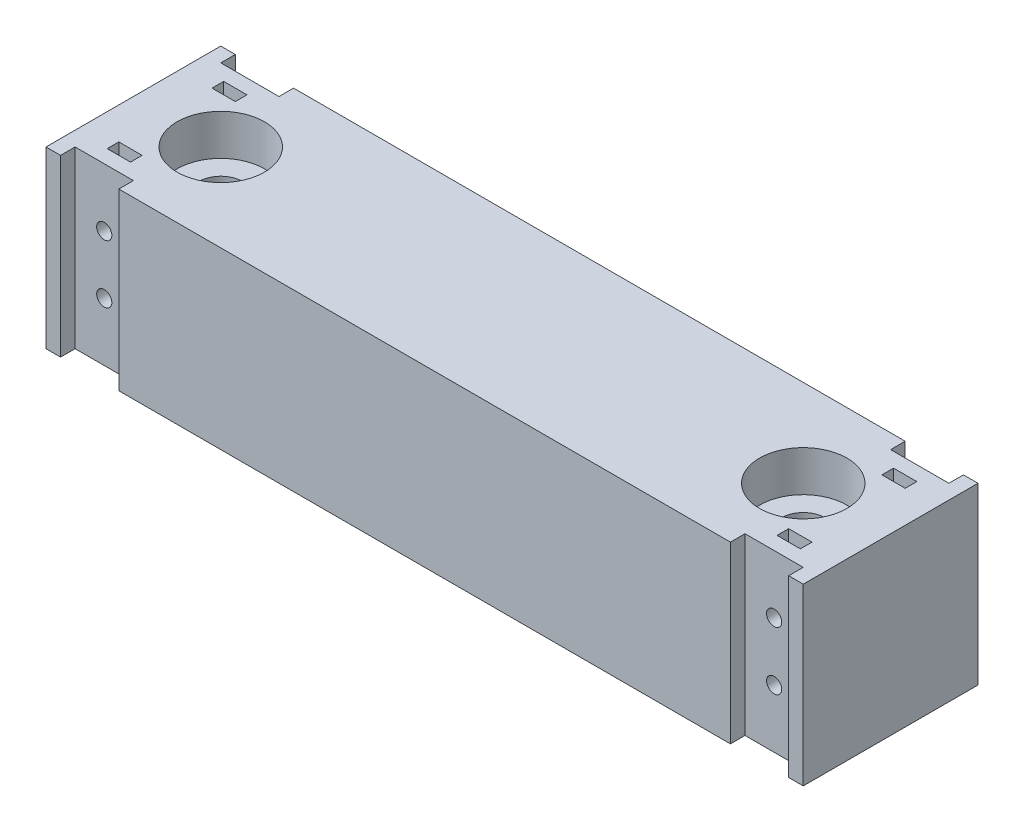
SolidWorks part; units mm, degrees
ref_plane "Płaszczyzna przednia" through (0, 0, 0) normal (0, 0, 1) x (1, 0, 0)
ref_plane "Płaszczyzna górna" through (0, 0, 0) normal (0, 1, 0) x (1, 0, 0)
ref_plane "Płaszczyzna prawa" through (0, 0, 0) normal (1, 0, 0) x (0, 0, -1)
sketch "Sketch1" plane through (0, 0, 0) normal (1, 0, 0) x (0, 0, -1)
  line L1 (0, 0) -> (60, 0)
  line L2 (0, 0) -> (0, 60)
  line L3 (0, 60) -> (60, 60)
  line L4 (60, 0) -> (60, 60)
  dimension "D1" = 60
  dimension "D2" = 60
extrude "Boss-Extrude1" add sketch "Sketch1" along normal blind 260
sketch "Sketch2" plane through (0, 0, 0) normal (0, 1, 0) x (1, 0, 0)
  line L0 (0, 60) -> (0, 0) construction
  line L1 (260, 0) -> (0, 0) construction
  line L2 (260, 60) -> (260, 0) construction
  circle A0 centre (30, 30) radius 7.5
  circle A1 centre (230, 30) radius 7.5
  dimension "D1" = 15
  dimension "D3" = 30
  dimension "D4" = 30
  dimension "D2" = 30
extrude "Cut-Extrude1" cut sketch "Sketch2" along normal through all both and the other way through all
sketch "Sketch3" plane through (0, 0, 0) normal (0, 1, 0) x (1, 0, 0)
  circle A0 centre (30, 30) radius 15
  circle A1 centre (230, 30) radius 15
  dimension "D1" = 30
extrude "Cut-Extrude2" cut sketch "Sketch3" against normal blind 14 from surface at 60 starting at face at (30, 60, -22.5)
sketch "Sketch4" plane through (0, 0, 0) normal (0, 0, 1) x (1, 0, 0)
  line L0 (260, 60) -> (0, 60) construction
  line L1 (5, 60) -> (25, 60)
  line L2 (5, 60) -> (5, 0)
  line L3 (5, 0) -> (25, 0)
  line L4 (25, 60) -> (25, 0)
  line L5 (260, 0) -> (0, 0) construction
  line L6 (0, 60) -> (0, 0) construction
  line L7 (260, 60) -> (260, 0) construction
  line L8 (235, 60) -> (255, 60)
  line L9 (235, 60) -> (235, 0)
  line L10 (235, 0) -> (255, 0)
  line L11 (255, 60) -> (255, 0)
  dimension "D1" = 20
  dimension "D2" = 5
  dimension "D3" = 5
  dimension "D4" = 20
extrude "Cut-Extrude3" cut sketch "Sketch4" against normal blind 5
sketch "Sketch5" plane through (0, 0, 0) normal (0, 0, 1) x (1, 0, 0)
  line L0 (15, 0) -> (15, 80) construction
  line L1 (5, 0) -> (25, 0) construction
  line L2 (25, 60) -> (5, 60) construction
  line L3 (130, 0) -> (130, 76.0371) construction
  line L4 (235, 0) -> (25, 0) construction
  line L5 (245, 0) -> (245, 80) construction
  circle A0 centre (15, 20) radius 2.6
  circle A1 centre (15, 40) radius 2.6
  circle A2 centre (245, 40) radius 2.6
  circle A3 centre (245, 20) radius 2.6
  dimension "D3" = 5.2
  dimension "D4" = 5.2
  dimension "D1" = 20
  dimension "D2" = 20
extrude "Cut-Extrude4" cut sketch "Sketch5" against normal through all both and the other way through all
ref_plane "Plane1" through (0, 0, -30) normal (0, 0, 1) x (1, 0, 0)
mirror "Mirror2" about plane through (0, 0, -30) normal (0, 0, 1) of "Cut-Extrude3"
sketch "Sketch6" plane through (0, 0, 0) normal (0, 0, 1) x (1, 0, 0)
  line L0 (11, 20) -> (11, 0)
  line L1 (19, 20) -> (17, 23.4641)
  line L2 (17, 23.4641) -> (13, 23.4641)
  line L3 (13, 23.4641) -> (11, 20)
  line L7 (5, 0) -> (25, 0) construction
  line L8 (11, 0) -> (19, 0)
  line L9 (19, 0) -> (19, 20)
  line L10 (130, 0) -> (130, 93.3639) construction
  line L11 (10.2178, 21.3548) -> (13.4291, 15.7927) [skipped]
  line L12 (11.4356, 16.5359) -> (17.8582, 16.5359) [skipped]
  line L13 (16.2178, 15.1811) -> (19.4291, 20.7432) [skipped]
  line L15 (0, 30) -> (260, 30) construction
  line L18 (19, 60) -> (19, 40)
  line L19 (11, 60) -> (19, 60)
  line L20 (13, 36.5359) -> (11, 40)
  line L21 (17, 36.5359) -> (13, 36.5359)
  line L22 (19, 40) -> (17, 36.5359)
  line L23 (11, 40) -> (11, 60)
  line L24 (249, 40) -> (249, 60)
  line L25 (241, 40) -> (243, 36.5359)
  line L26 (243, 36.5359) -> (247, 36.5359)
  line L27 (247, 36.5359) -> (249, 40)
  line L28 (249, 60) -> (241, 60)
  line L29 (241, 60) -> (241, 40)
  line L30 (241, 0) -> (241, 20)
  line L31 (249, 0) -> (241, 0)
  line L32 (247, 23.4641) -> (249, 20)
  line L33 (243, 23.4641) -> (247, 23.4641)
  line L34 (241, 20) -> (243, 23.4641)
  line L35 (249, 20) -> (249, 0)
  circle A0 centre (15, 20) radius 3.4641 construction
  circle A1 centre (15, 40) radius 3.4641 construction
  circle A2 centre (245, 40) radius 3.4641 construction
  circle A3 centre (245, 20) radius 3.4641 construction
  dimension "D1" = 8
extrude "Cut-Extrude5" cut sketch "Sketch6" against normal blind 4 from offset 10 offset against normal yes
mirror "Mirror3" about plane through (0, 0, -30) normal (0, 0, 1) of "Cut-Extrude5"
